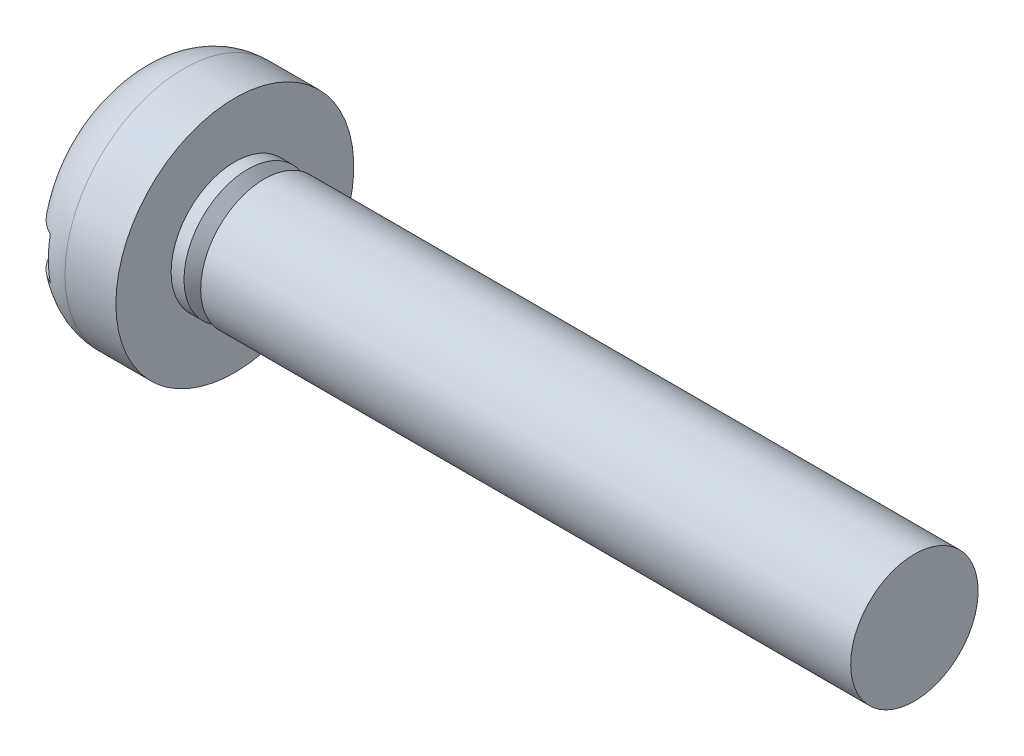
SolidWorks part; units mm, degrees
ref_plane "Plane1" through (0, 0, 0) normal (0, 0, 1) x (1, 0, 0)
ref_plane "Plane2" through (0, 0, 0) normal (0, 1, 0) x (1, 0, 0)
ref_plane "Plane3" through (0, 0, 0) normal (1, 0, 0) x (0, 0, -1)
sketch "BodySke" plane through (0, 0, 0) normal (0, 0, 1) x (1, 0, 0)
  line L0 (2.4, 1.5) -> (2.4, 2.8)
  line L1 (0, 0) -> (0, 1.6)
  line L2 (-25.4, 0) -> (127, 0) construction
  line L3 (18.4, 0) -> (0, 0)
  line L4 (2.4, 1.5) -> (18.4, 1.5)
  line L5 (18.4, 1.5) -> (18.4, 0)
  line L6 (1.2, 2.8) -> (2.4, 2.8)
  line L7 (2.4, -1.5) -> (18.4, -1.5) construction
  line L8 (0, -2.8) -> (2.4, -2.8) construction
  line L9 (2.9, 3.0875) -> (2.9, -6.4375) construction
  line L10 (-3.6, 6.35) -> (-3.6, -3.175) construction
  arc A0 (0, 1.6) -> (1.2, 2.8) centre (1.2, 1.6) cw
  point P15 (0, 2.8)
  dimension "Head_fillet_rad" = 1.2
  dimension "Head_ht" = 2.4
  dimension "Diameter" = 3
  dimension "Length" = 16
  dimension "Head_dia" = 5.6
  dimension "Advance" = 0.5
  dimension "Thread_nom" = 22
revolve "Base-Revolve" add sketch "BodySke" angle 360 about L2
cosmetic thread "ThreadCosmetic" [suppressed] parameters "Thread_length"=15.5, "Thread_minor"=2.439
sketch "Sketch2" plane through (0, 0, 0) normal (1, 0, 0) x (0, 0, -1)
  line L0 (2.8, -0.5) -> (-2.8, -0.5)
  line L1 (2.8, -0.5) -> (2.8, 0.5)
  line L2 (-2.8, 0.5) -> (2.8, 0.5)
  line L3 (-2.8, 0.5) -> (-2.8, -0.5)
  dimension "D1" = 5.6
  dimension "D2" = 2.8
  dimension "Slot_width" = 1
  dimension "D3" = 0.5
extrude "Slot" cut sketch "Sketch2" along normal blind 0.7
sketch "ThdSchSke" plane through (0, 0, 0) normal (0, 0, 1) x (1, 0, 0)
  line L0 (2.9, -1.2195) -> (2.7036, -1.5)
  line L1 (2.9, -1.2195) -> (3.0964, -1.5)
  line L2 (3.0964, -1.5) -> (3.0964, -1.875)
  line L3 (-3.175, 0) -> (5.1513, 0) construction
  line L5 (3.0964, -1.875) -> (2.7036, -1.875)
  line L6 (2.7036, -1.875) -> (2.7036, -1.5)
  dimension "Thread_minor" = 2.439
  dimension "Diameter" = 3
  dimension "Start" = 2.9
  dimension "SideAngle" = 55
  dimension "VeeAngle" = 70
  dimension "Overcut" = 3.75
revolve "ThreadSchematic" cut sketch "ThdSchSke" angle 360 about L3
pattern_linear "ThdSchPat" [suppressed]
equation "\"D1@Sketch2\" = \"Head_dia@BodySke\""
equation "\"D2@Sketch2\" = \"D1@Sketch2\" / 2"
equation "\"D3@Sketch2\" = \"Slot_width@Sketch2\" / 2"
equation "\"Thread_length@ThreadCosmetic\" = ((sgn( (\"Length@BodySke\" - \"Advance@BodySke\" ) - \"Thread_nom@BodySke\" )-1)*( (\"Length@BodySke\" - \"Advance@BodySke\" ) - \"Thread_nom@BodySke\" ))/-2+ \"Thread_nom@BodySke\""
equation "\"Thread_minor@ThdSchSke\" = \"Thread_minor@ThreadCosmetic\""
equation "\"Diameter@ThdSchSke\" = \"Diameter@BodySke\""
equation "\"Overcut@ThdSchSke\" = \"Diameter@BodySke\" * 1.25"
equation "\"Start@ThdSchSke\" = \"Head_ht@BodySke\" + \"Length@BodySke\" - \"Thread_length@ThreadCosmetic\"  '---Non-countersunk---"
equation "\"Num_threads@ThdSchPat\" = int( \"Thread_length@ThreadCosmetic\" / \"Advance@BodySke\" + 0.999 )  + 1"
equation "\"Advance@ThdSchPat\" = \"Thread_length@ThreadCosmetic\" /  (\"Num_threads@ThdSchPat\" - 1) 'relax it"
